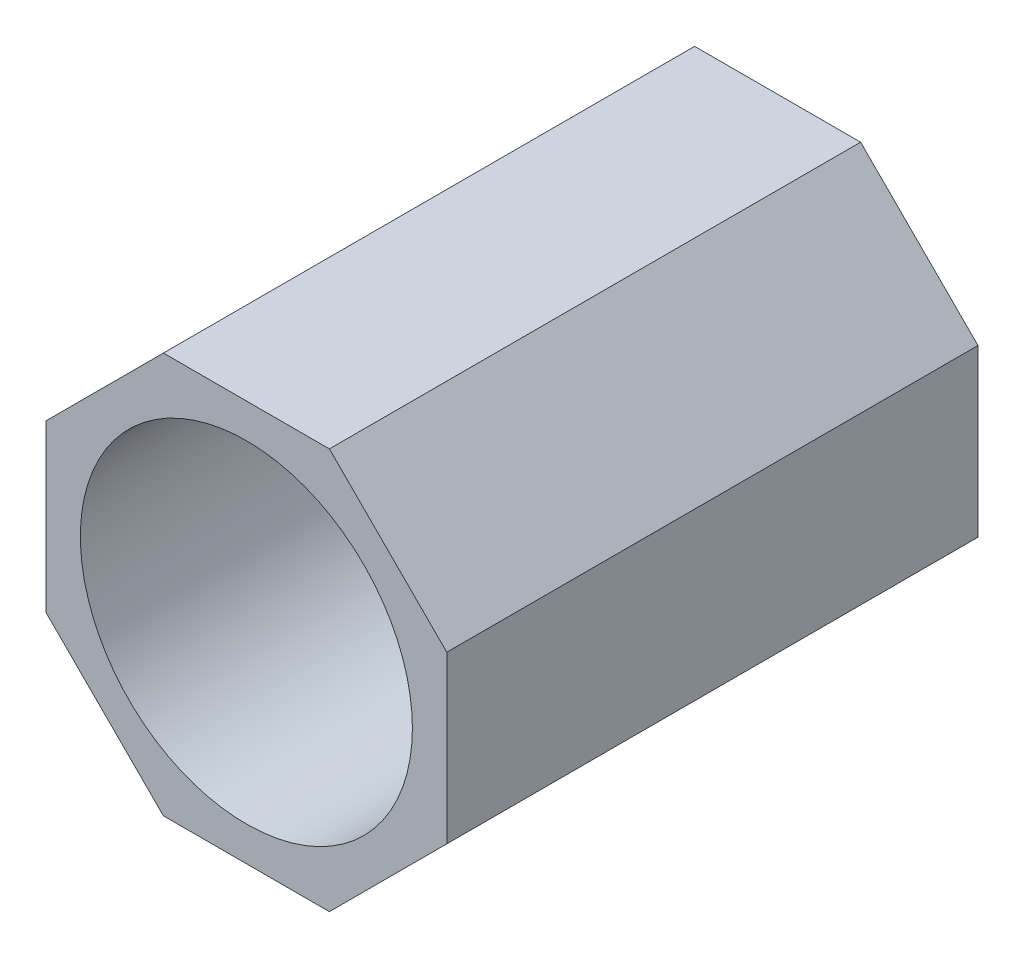
SolidWorks part; units mm, degrees
ref_plane "Front Plane" through (0, 0, 0) normal (0, 0, 1) x (1, 0, 0)
ref_plane "Top Plane" through (0, 0, 0) normal (0, 1, 0) x (1, 0, 0)
ref_plane "Right Plane" through (0, 0, 0) normal (1, 0, 0) x (0, 0, -1)
sketch "Sketch1" plane through (0, 0, 0) normal (0, 0, 1) x (1, 0, 0)
  line L0 (-1.25, 3.0178) -> (1.25, 3.0178)
  line L1 (1.25, 3.0178) -> (3.0178, 1.25)
  line L2 (3.0178, 1.25) -> (3.0178, -1.25)
  line L3 (3.0178, -1.25) -> (1.25, -3.0178)
  line L4 (1.25, -3.0178) -> (-1.25, -3.0178)
  line L5 (-1.25, -3.0178) -> (-3.0178, -1.25)
  line L6 (-3.0178, -1.25) -> (-3.0178, 1.25)
  line L7 (-3.0178, 1.25) -> (-1.25, 3.0178)
  line L8 (1.25, 3.0178) -> (-1.25, -3.0178) construction
  line L9 (-1.25, 3.0178) -> (1.25, -3.0178) construction
  circle A0 centre (0, 0) radius 2.5
  point P7 (0, 0)
  point P9 (0, 0)
  dimension "D1" = 5
  dimension "D2" = 2.5
extrude "Boss-Extrude1" add sketch "Sketch1" along normal blind 8
